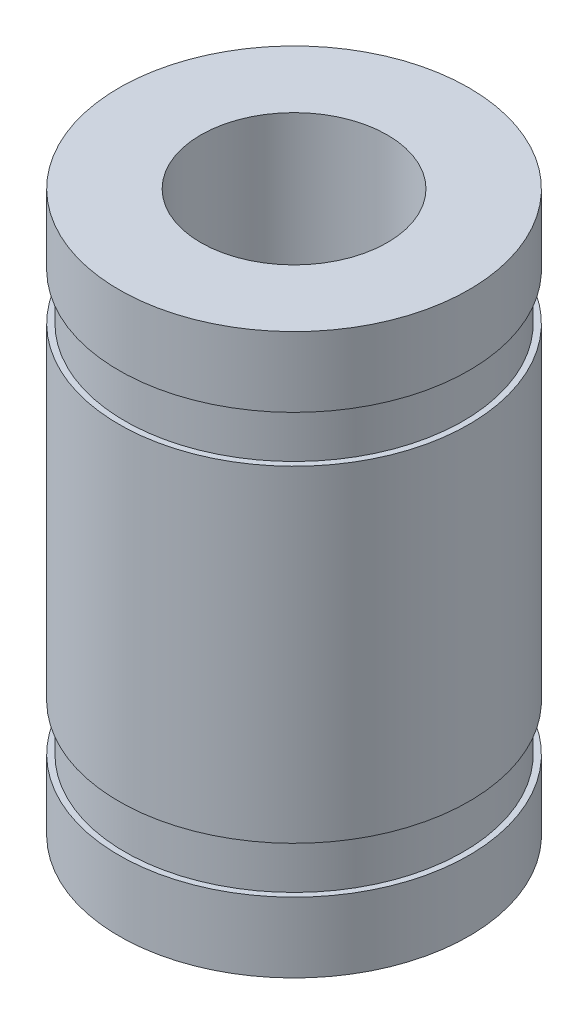
SolidWorks part; units mm, degrees
ref_plane "Front Plane" through (0, 0, 0) normal (0, 0, 1) x (1, 0, 0)
ref_plane "Top Plane" through (0, 0, 0) normal (0, 1, 0) x (1, 0, 0)
ref_plane "Right Plane" through (0, 0, 0) normal (1, 0, 0) x (0, 0, -1)
sketch "Sketch1" plane through (0, 0, 0) normal (0, 0, 1) x (1, 0, 0)
  line L0 (0, -6.0586) -> (0, 8.8716) construction
  line L1 (4, 0) -> (4, -12)
  line L2 (4, -12) -> (7.5, -12)
  line L3 (7.5, -12) -> (7.5, -9)
  line L4 (7.5, -9) -> (7.25, -9)
  line L5 (7.25, -9) -> (7.25, -7)
  line L6 (7.25, -7) -> (7.5, -7)
  line L7 (7.5, -7) -> (7.5, 0)
  line L8 (7.5, 0) -> (4, 0)
  line L9 (0, 0) -> (4.875, 0) construction
  line L10 (4, 0) -> (4.1072, -0.1425) construction
  point P14 (7.25, -8)
  dimension "D1" = 12
  dimension "D2" = 8
  dimension "D3" = 15
  dimension "D4" = 14.5
  dimension "D5" = 2
  dimension "D6" = 8
revolve "Revolve1" add sketch "Sketch1" angle 360 about L0
mirror "Mirror1" about plane through (0, 0, 0) normal (0, 1, 0) of "Revolve1"
